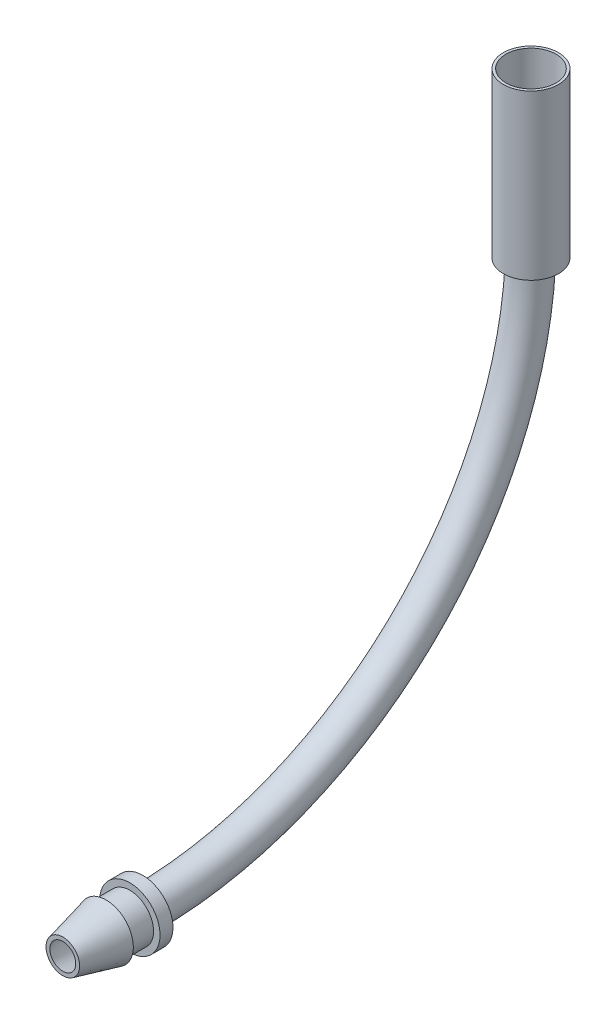
SolidWorks part; units mm, degrees
ref_plane "Front Plane" through (0, 0, 0) normal (0, 0, 1) x (1, 0, 0)
ref_plane "Top Plane" through (0, 0, 0) normal (0, 1, 0) x (1, 0, 0)
ref_plane "Right Plane" through (0, 0, 0) normal (1, 0, 0) x (0, 0, -1)
sketch "Sketch1" plane through (0, 0, 0) normal (1, 0, 0) x (0, 0, -1)
  arc A0 (0, -45) -> (45, 0) centre (0, 0) ccw
  dimension "D1" = 45
ref_plane "Plane1" through (0, -45, 0) normal (0, 0, -1) x (-1, 0, 0)
sketch "Sketch2" plane through (0, -45, 0) normal (0, 0, -1) x (-1, 0, 0)
  line L0 (0, 45) -> (0, 0) construction
  circle A0 centre (0, 0) radius 1.5
  dimension "D1" = 3
sweep "Sweep-Thin1" add profiles "Sketch2" path "Sketch1" parameters "D1"=0.57
sketch "Sketch3" plane through (0, 0, 0) normal (0, 0, 1) x (1, 0, 0)
  circle A0 centre (0, -45) radius 2.75
  circle A1 centre (0, -45) radius 1.5
  dimension "D1" = 3
  dimension "D2" = 5.5
extrude "Boss-Extrude1" add sketch "Sketch3" along normal blind 4.5
sketch "Sketch4" plane through (0, -45, 0) normal (0, 0, -1) x (-1, 0, 0)
  circle A0 centre (0, 0) radius 2.5
  circle A1 centre (0, 0) radius 3.5
  dimension "D1" = 5
  dimension "D2" = 7
extrude "Boss-Extrude2" add sketch "Sketch4" against normal blind 1.5
sketch "Sketch5" plane through (0, 0, 0) normal (0, 1, 0) x (1, 0, 0)
  line L0 (0, 0) -> (0, 45) construction
  circle A0 centre (0, 45) radius 3.2
  circle A1 centre (0, 45) radius 1.5
  circle A3 centre (0, 45) radius 1.5 construction
  point P8 (0, 45)
  dimension "D1" = 6.4
extrude "Boss-Extrude3" add sketch "Sketch5" along normal blind 1 and the other way blind 2 separate body
sketch "Sketch6" plane through (0, 1, 0) normal (0, 1, 0) x (1, 0, 0)
  circle A0 centre (0, 45) radius 3.5
  circle A1 centre (0, 45) radius 4
  dimension "D1" = 7
  dimension "D2" = 8
extrude "Boss-Extrude4" [suppressed] add sketch "Sketch6" along normal blind 16
sketch "Sketch8" plane through (0, 0, 0) normal (1, 0, 0) x (0, 0, -1)
  line L0 (-4.2571, -42.3511) -> (-4.2571, -41.8381)
  line L1 (-4.2571, -41.8381) -> (-9.2715, -43.0531)
  line L2 (-9.2715, -43.0531) -> (-9.2715, -43.5)
  line L3 (-9.2715, -43.5) -> (-4.2571, -42.3511)
  line L4 (-4.5, -42.25) -> (-4.5, -47.75) construction
  line L5 (-4.5, -45) -> (-9.2715, -45) construction
  point P2 (-4.5, -45)
  point P5 (-4.5, -42.5566)
  point P9 (-4.2571, -42.3511)
  point P12 (-4.2571, -41.7663)
  dimension "D1" = 1.5
  dimension "D2" = 0.5
revolve "Revolve1" add sketch "Sketch8" angle 360 about L5
sketch "Sketch9" [suppressed] plane through (0, 0, 0) normal (1, 0, 0) x (0, 0, -1)
  line L0 (-9.2715, -45) -> (-9.2715, 17)
  line L1 (-9.2715, -43.0531) -> (-9.2715, -46.9469) construction
  line L2 (-9.2715, 17) -> (45, 17)
  line L3 (48.5, 17) -> (41.5, 17) construction
sketch "Sketch10" plane through (0, 1, 0) normal (0, 1, 0) x (1, 0, 0)
  circle A0 centre (0, 45) radius 3.2
  circle A1 centre (0, 45) radius 2.9
  circle A2 centre (0, 45) radius 3.2 construction
  dimension "D1" = 0.3
extrude "Boss-Extrude6" add sketch "Sketch10" along normal blind 16 and the other way blind 1
